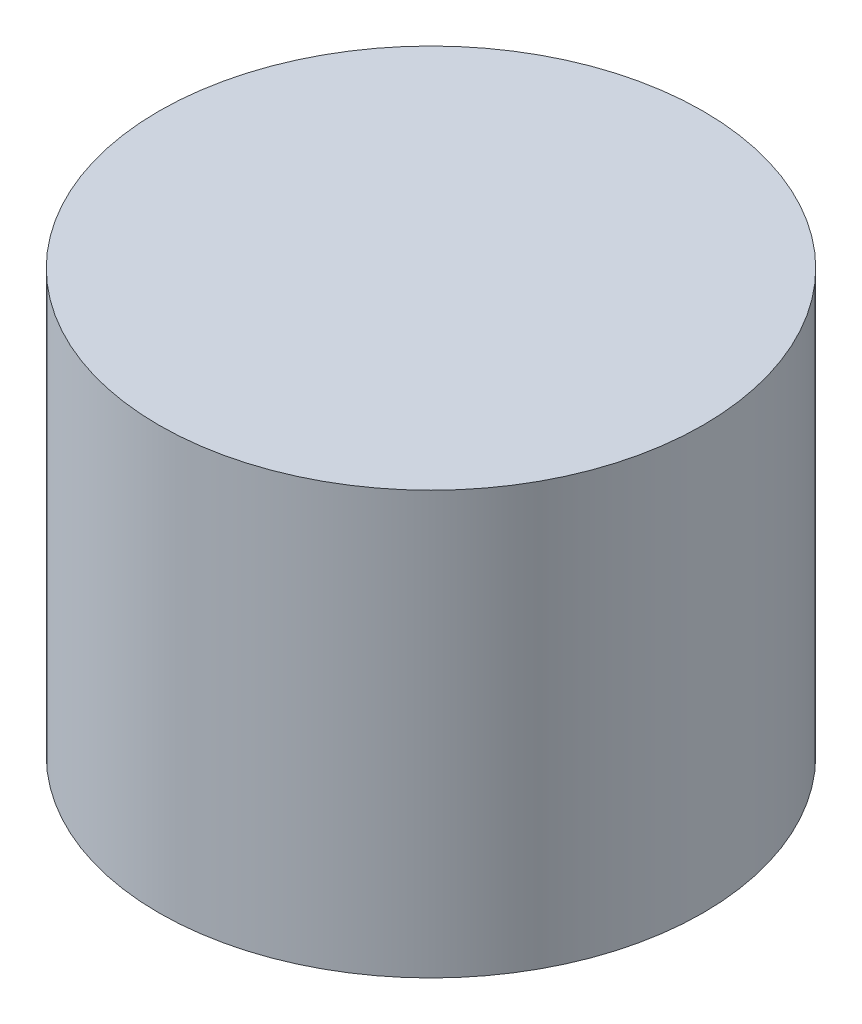
SolidWorks part; units mm, degrees
ref_plane "前视基准面" through (0, 0, 0) normal (0, 0, 1) x (1, 0, 0)
ref_plane "上视基准面" through (0, 0, 0) normal (0, 1, 0) x (1, 0, 0)
ref_plane "右视基准面" through (0, 0, 0) normal (1, 0, 0) x (0, 0, -1)
ref_plane "基准面4" through (0, 0, 0) normal (0, 0, -1) x (-1, 0, 0)
sketch "草图1" plane through (0, 0, 0) normal (0, 0, -1) x (-1, 0, 0)
  line L0 (-1.9, 0) -> (0, 0)
  line L1 (0, 0) -> (0, 2.95)
  line L2 (0, 2.95) -> (-1.9, 2.95)
  line L3 (-1.9, 2.95) -> (-1.9, 0)
  line L4 (0, 0) -> (0, 2.95) construction
revolve "旋转1" add sketch "草图1" angle 360 about L4
